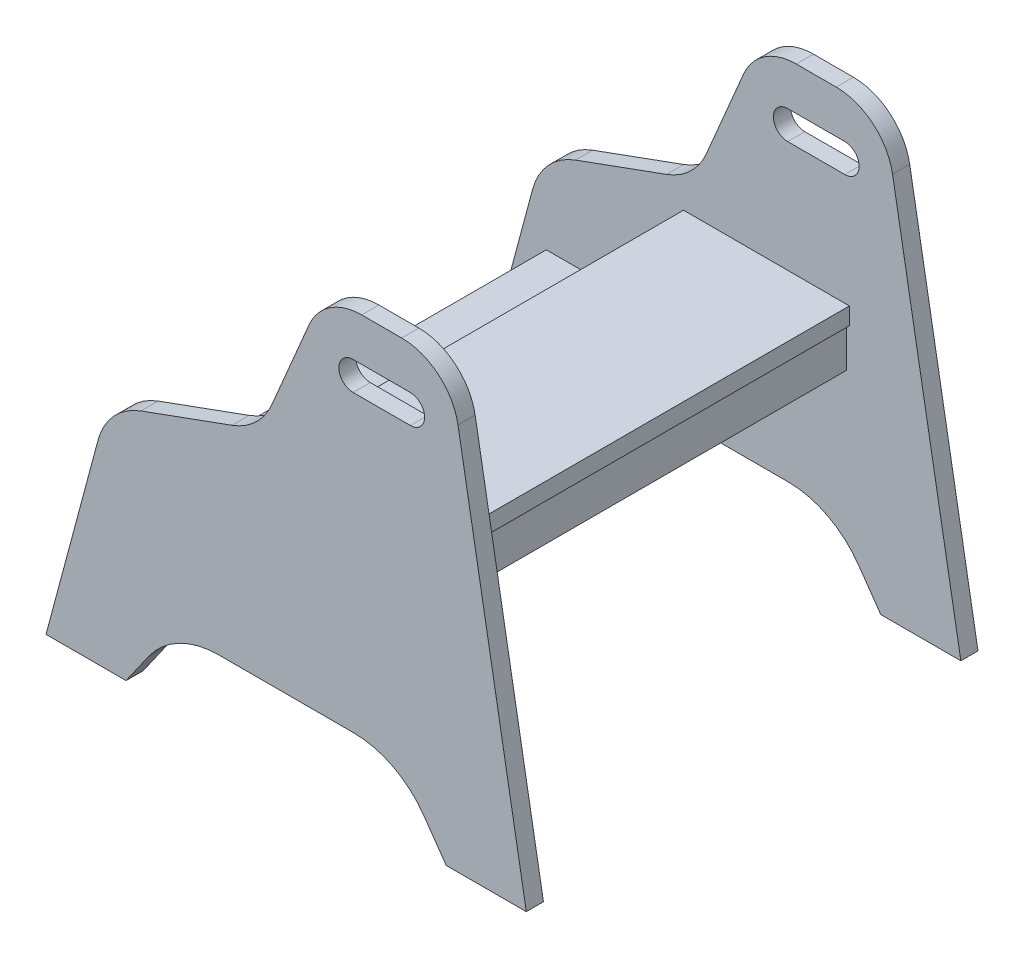
SolidWorks part; units mm, degrees
material "Beech"
ref_plane "Front Plane" through (0, 0, 0) normal (0, 0, 1) x (1, 0, 0)
ref_plane "Top Plane" through (0, 0, 0) normal (0, 1, 0) x (1, 0, 0)
ref_plane "Right Plane" through (0, 0, 0) normal (1, 0, 0) x (0, 0, -1)
sketch "Sketch1" plane through (0, 0, 0) normal (0, 0, 1) x (1, 0, 0)
  line L0 (0, 0) -> (45.5059, 169.8303)
  line L1 (82.9402, 210.6827) -> (162.7231, 239.7213)
  line L2 (197.4322, 272.6589) -> (230.0648, 349.5366)
  line L3 (276.09, 380) -> (311.0408, 380)
  line L4 (360.2812, 338.6824) -> (420, 0)
  line L5 (420, 0) -> (350, 0)
  line L6 (268.945, 60) -> (151.055, 60)
  line L7 (70, 0) -> (0, 0)
  line L8 (70, 0) -> (89.6186, 28.0182)
  line L9 (330.3814, 28.0182) -> (350, 0)
  line L10 (268.5654, 330) -> (318.5654, 330) construction
  line L11 (268.5654, 342.5) -> (318.5654, 342.5)
  line L12 (268.5654, 317.5) -> (318.5654, 317.5)
  line L13 (293.5654, 380) -> (293.5654, 330) construction
  arc A6 (330.3814, 28.0182) -> (268.945, 60) centre (268.945, -15) ccw
  arc A7 (151.055, 60) -> (89.6186, 28.0182) centre (151.055, -15) ccw
  arc A8 (82.9402, 210.6827) -> (45.5059, 169.8303) centre (103.4614, 154.3011) ccw
  arc A9 (360.2812, 338.6824) -> (311.0408, 380) centre (311.0408, 330) ccw
  arc A10 (276.09, 380) -> (230.0648, 349.5366) centre (276.09, 330) ccw
  arc A11 (197.4322, 272.6589) -> (162.7231, 239.7213) centre (142.2019, 296.1028) cw
  arc A12 (268.5654, 342.5) -> (268.5654, 317.5) centre (268.5654, 330) ccw
  arc A13 (318.5654, 317.5) -> (318.5654, 342.5) centre (318.5654, 330) ccw
  point P4 (293.5654, 330)
  point P23 (53.5898, 200)
  point P26 (352.9957, 380)
  point P29 (242.9957, 380)
  dimension "D11" = 75
  dimension "D12" = 60
  dimension "D15" = 50
  dimension "D16" = 60
  dimension "D19" = 12.5
  dimension "D1" = 420
  dimension "D2" = 60
  dimension "D3" = 55
  dimension "D4" = 55
  dimension "D5" = 70
  dimension "D6" = 200
  dimension "D7" = 80
  dimension "D8" = 75
  dimension "D9" = 125
  dimension "D10" = 110
  dimension "D13" = 380
  dimension "D14" = 113
  dimension "D17" = 50
  dimension "D18" = 50
extrude "Boss-Extrude1" add sketch "Sketch1" along normal blind 15
sketch "Sketch3" plane through (0, 0, 15) normal (0, 0, 1) x (1, 0, 0)
  line L0 (200, 115) -> (202.5, 115)
  line L1 (177.5, 220) -> (322.5, 220)
  line L2 (177.5, 220) -> (177.5, 205)
  line L3 (177.5, 205) -> (180, 205)
  line L4 (322.5, 220) -> (322.5, 205)
  line L6 (180, 205) -> (180, 170)
  line L7 (180, 170) -> (320, 170)
  line L8 (320, 205) -> (320, 170)
  line L9 (57.5, 130) -> (202.5, 130)
  line L10 (57.5, 130) -> (57.5, 115)
  line L11 (57.5, 115) -> (60, 115)
  line L12 (202.5, 130) -> (202.5, 115)
  line L14 (60, 115) -> (60, 80)
  line L15 (60, 80) -> (200, 80)
  line L16 (200, 115) -> (200, 80)
  line L17 (320, 205) -> (322.5, 205)
  line L18 (151.055, 60) -> (268.945, 60) construction
  point P16 (207.332, 78.6954)
  dimension "D1" = 145
  dimension "D2" = 140
  dimension "D3" = 15
  dimension "D4" = 35
  dimension "D5" = 15
  dimension "D6" = 35
  dimension "D7" = 145
  dimension "D8" = 140
  dimension "D9" = 60
  dimension "D10" = 40
  dimension "D11" = 20
  dimension "D12" = 120
extrude "Boss-Extrude2" add sketch "Sketch3" along normal blind 365
ref_plane "Plane4" through (0, 0, 197.5) normal (0, 0, 1) x (1, 0, 0)
mirror "Mirror1" about plane through (0, 0, 197.5) normal (0, 0, 1) of "Boss-Extrude1"
equation "\"A\"= 420"
equation "\"D1@Sketch1\"=\"A\""
equation "\"C\" = 200"
equation "\"D6@Sketch1\"=\"C\""
equation "\"B\"= 380"
equation "\"D13@Sketch1\"=\"B\""
